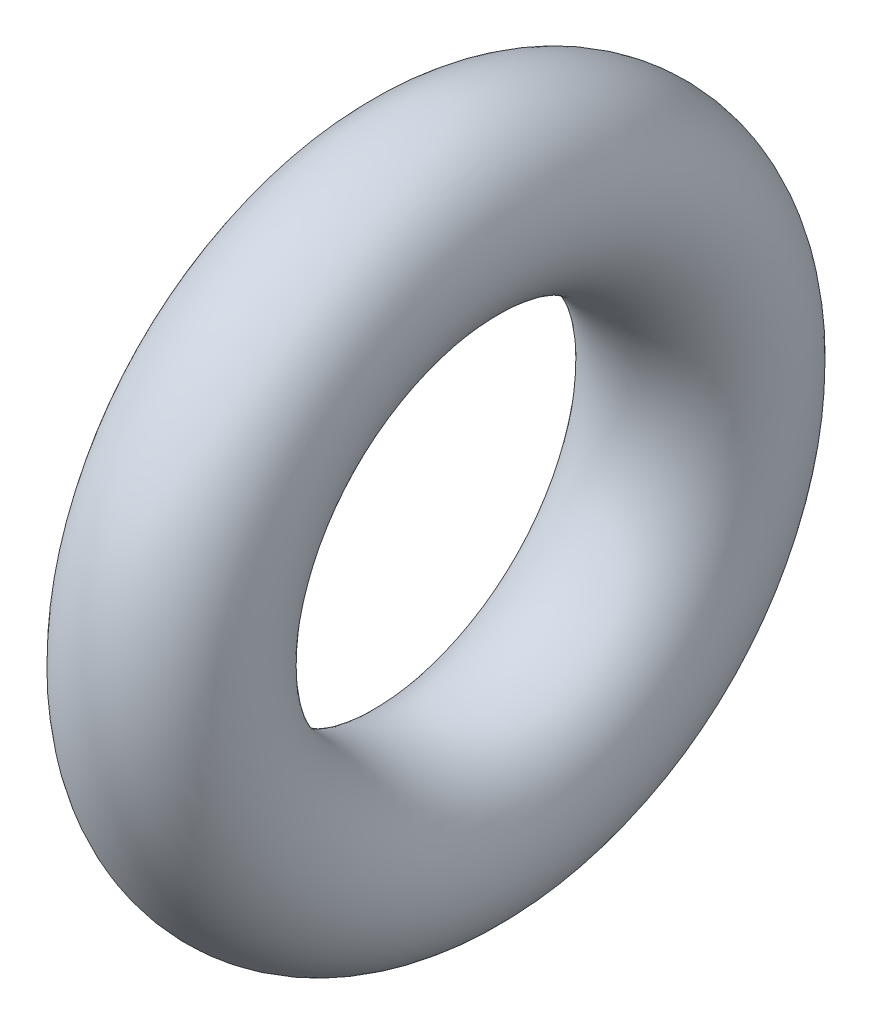
SolidWorks part; units mm, degrees
ref_plane "Plan de face" through (0, 0, 0) normal (0, 0, 1) x (1, 0, 0)
ref_plane "Plan de dessus" through (0, 0, 0) normal (0, 1, 0) x (1, 0, 0)
ref_plane "Plan de droite" through (0, 0, 0) normal (1, 0, 0) x (0, 0, -1)
sketch "Esquisse1" plane through (0, 0, 0) normal (0, 0, 1) x (1, 0, 0)
  line L0 (8.3332, 0) -> (23.2219, 0) construction
  circle A0 centre (15.6319, 7.5) radius 2.5
  arc A1 (17.9232, 8.5) -> (13.3406, 8.5) centre (15.6319, 7.5) ccw construction
revolve "Révolution1" add sketch "Esquisse1" angle 360 about L0
